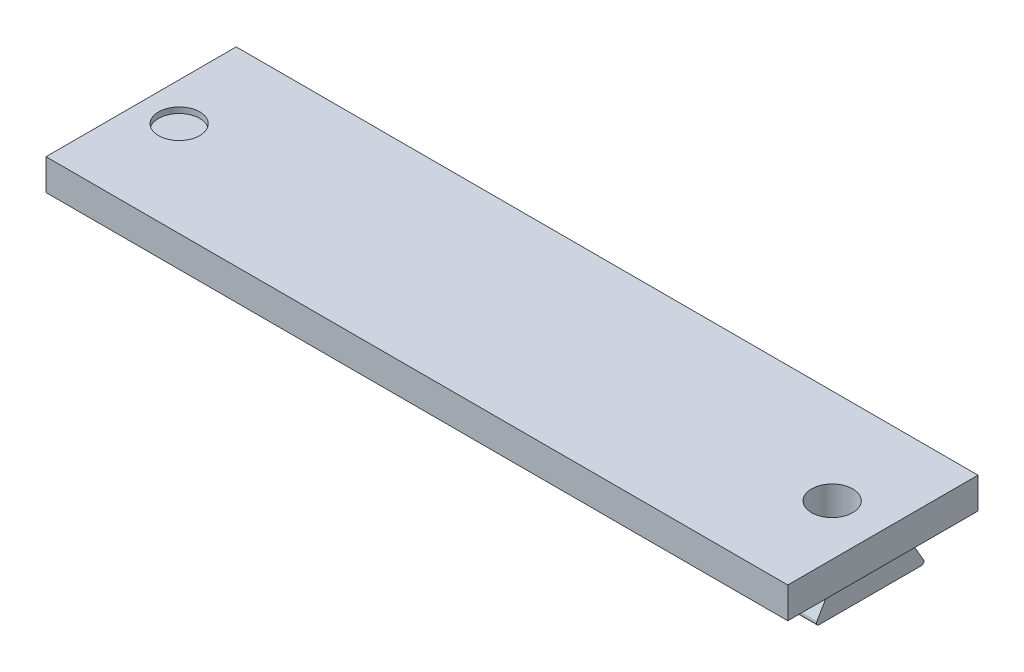
SolidWorks part; units mm, degrees
ref_plane "Front Plane" through (0, 0, 0) normal (0, 0, 1) x (1, 0, 0)
ref_plane "Top Plane" through (0, 0, 0) normal (0, 1, 0) x (1, 0, 0)
ref_plane "Right Plane" through (0, 0, 0) normal (1, 0, 0) x (0, 0, -1)
sketch "Sketch4" plane through (0, 0, 0) normal (1, 0, 0) x (0, 0, -1)
  line L0 (0, 0) -> (0, -5) construction
  line L1 (8.9434, -5) -> (-8.9434, -5) construction
  line L2 (-8.9434, -5) -> (-6.0566, 0) construction
  line L3 (8.9434, -5) -> (6.0566, 0) construction
  line L4 (-6.0566, 0) -> (-15, 0) construction
  line L5 (6.0566, 0) -> (15, 0) construction
  line L6 (-15, 0) -> (-15, 5) construction
  line L7 (15, 0) -> (15, 5) construction
  line L8 (-15, 5) -> (15, 5)
  line L9 (-6.0566, 0) -> (0, 0) construction
  line L10 (6.0566, 0) -> (0, 0) construction
  line L11 (-8.9434, -5) -> (-15, -5) construction
  line L12 (8.9434, -5) -> (15, -5) construction
  line L13 (-15, 0) -> (-15, -5) construction
  line L14 (15, -5) -> (15, 0) construction
  line L15 (5.8834, 0.1) -> (15, 0.1)
  line L16 (8.7702, -4.9) -> (5.8834, 0.1)
  line L17 (8.7702, -4.9) -> (-8.7702, -4.9)
  line L18 (-8.7702, -4.9) -> (-5.8834, 0.1)
  line L19 (-5.8834, 0.1) -> (-15, 0.1)
  line L20 (-15, 5) -> (-15, 0.1)
  line L21 (15, 5) -> (15, 0.1)
  dimension "D1" = 5
  dimension "D2" = 30
  dimension "D3" = 5
  dimension "D4" = 30
  dimension "D5" = 0.1
extrude "Boss-Extrude2" add sketch "Sketch4" along normal mid plane 115
fillet "Fillet1" radius 0.4 2 edges at (0, -4.9, -8.7702) (0, -4.9, 8.7702)
fillet "Fillet2" radius 0.5 2 edges at (0, 0.1, -5.8834) (0, 0.1, 5.8834)
sketch "Sketch5" plane through (0, -4.9, 0) normal (0, -1, 0) x (1, 0, 0)
  line L0 (0, 0) -> (51.5, 0) construction
  line L1 (57.5, 8.0774) -> (57.5, -8.0774) construction
  circle A0 centre (51.5, 0) radius 4.25
  dimension "D1" = 8.5
  dimension "D2" = 6
extrude "Cut-Extrude1" cut sketch "Sketch5" against normal blind 3
sketch "Sketch6" plane through (0, 5, 0) normal (0, 1, 0) x (1, 0, 0)
  circle A0 centre (51.5, 0) radius 3.25
  circle A1 centre (51.5, 0) radius 4.25 construction
  dimension "D1" = 6.5
extrude "Cut-Extrude2" cut sketch "Sketch6" against normal offset from surface (5.9 mm away) 1 contours A0 up to face at (51.5, -1.9, -4.25)
sketch "Sketch7" plane through (0, -4.9, 0) normal (0, -1, 0) x (1, 0, 0)
  line L0 (-51.5, 0) -> (0, 0) construction
  line L1 (-57.5, 8.0774) -> (-57.5, -8.0774) construction
  circle A0 centre (-51.5, 0) radius 4.25
  circle A2 centre (51.5, 0) radius 4.25 construction
  dimension "D1" = 6
extrude "Cut-Extrude3" cut sketch "Sketch7" against normal blind 8
sketch "Sketch8" plane through (0, 5, 0) normal (0, 1, 0) x (1, 0, 0)
  circle A0 centre (-51.5, 0) radius 3.25
  circle A1 centre (-51.5, 0) radius 4.25 construction
  circle A2 centre (51.5, 0) radius 3.25 construction
extrude "Cut-Extrude4" cut sketch "Sketch8" against normal offset from surface (0.9 mm away) 1 up to face at (-51.5, 3.1, -4.25)
sketch "Sketch9" plane through (57.5, 0, 0) normal (1, 0, 0) x (0, 0, -1)
  line L7 (-15, 5) -> (15, 5)
  line L8 (-15, 5) -> (-15, 0.1)
  line L9 (-15, 0.1) -> (15, 0.1)
  line L10 (15, 5) -> (15, 0.1)
extrude "Boss-Extrude3" add sketch "Sketch9" along normal blind 2
chamfer "Chamfer1" distance 0.5 angle 45 2 edges at (51.5, -4.9, -4.25) (-51.5, -4.9, -4.25)
